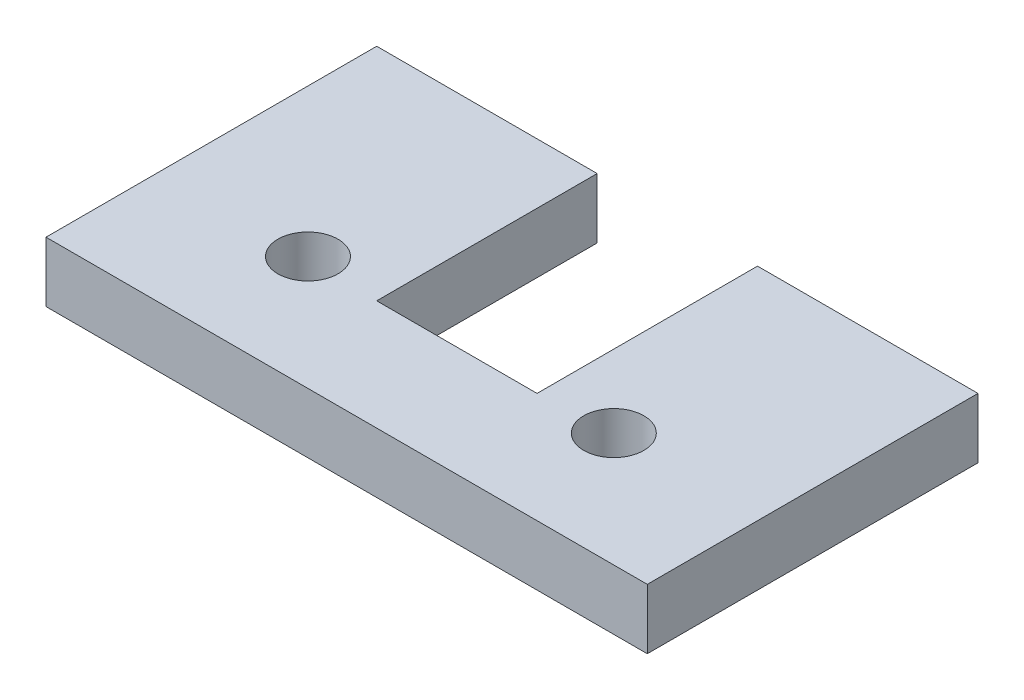
SolidWorks part; units mm, degrees
ref_plane "Front Plane" through (0, 0, 0) normal (0, 0, 1) x (1, 0, 0)
ref_plane "Top Plane" through (0, 0, 0) normal (0, 1, 0) x (1, 0, 0)
ref_plane "Right Plane" through (0, 0, 0) normal (1, 0, 0) x (0, 0, -1)
sketch "Sketch1" plane through (0, 0, 0) normal (0, 1, 0) x (1, 0, 0)
  line L0 (-4, 0) -> (-4, -5.5) construction
  line L1 (0, 0) -> (-8, 0)
  line L2 (0, 0) -> (0, -11)
  line L3 (0, -11) -> (-8, -11)
  line L4 (-8, 0) -> (-8, -11)
  line L5 (-19, 0) -> (11, 0)
  line L6 (-19, 0) -> (-19, -16.5)
  line L7 (-19, -16.5) -> (11, -16.5)
  line L8 (11, 0) -> (11, -16.5)
  line L9 (-19, 0) -> (11, -16.5) construction
  line L10 (-19, -16.5) -> (11, 0) construction
  line L11 (-4, -5.5) -> (-4, -13.3) construction
  line L12 (-14.13, -13.3) -> (6.13, -13.3) construction
  line L13 (6.13, -13.3) -> (6.13, 2.3) construction
  line L14 (6.13, -13.3) -> (3.63, -13.3) construction
  line L15 (3.63, -13.3) -> (3.63, -10.8) construction
  line L16 (-4, -5.5) -> (6.13, -5.5) construction
  line L17 (-14.13, -13.3) -> (-14.13, 2.3) construction
  line L18 (-14.13, 2.3) -> (6.13, 2.3) construction
  line L19 (-4, -8.25) -> (-4, -16.5) construction
  circle A0 centre (3.63, -10.8) radius 1.5
  circle A1 centre (-11.63, -10.8) radius 1.5
  point P5 (-5.5139, -5.5)
  point P28 (-14.13, -5.5)
  dimension "D10" = 3
  dimension "D1" = 8
  dimension "D2" = 11
  dimension "D3" = 30
  dimension "D4" = 16.5
  dimension "D5" = 5.5
  dimension "D6" = 7.8
  dimension "D7" = 10.13
  dimension "D8" = 2.5
  dimension "D9" = 2.5
extrude "Boss-Extrude1" add sketch "Sketch1" along normal blind 3 contours L8 L5 L2 L3 L4 L6 L7 A0 A1
